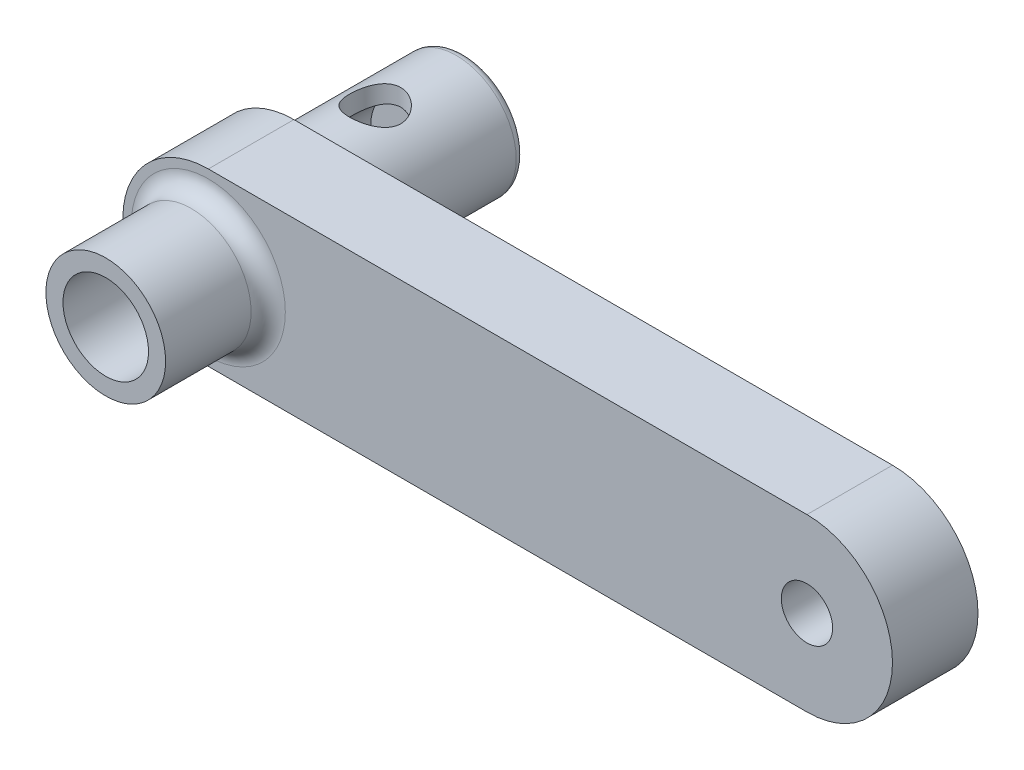
SolidWorks part; units mm, degrees
ref_plane "Plan de face" through (0, 0, 0) normal (0, 0, 1) x (1, 0, 0)
ref_plane "Plan de dessus" through (0, 0, 0) normal (0, 1, 0) x (1, 0, 0)
ref_plane "Plan de droite" through (0, 0, 0) normal (1, 0, 0) x (0, 0, -1)
sketch "Esquisse1" plane through (0, 0, 0) normal (0, 0, 1) x (1, 0, 0)
  line L0 (-17.5, 0) -> (17.5, 0) construction
  line L1 (-17.5, 5) -> (17.5, 5)
  line L2 (-17.5, -5) -> (17.5, -5)
  arc A0 (-17.5, 5) -> (-17.5, -5) centre (-17.5, 0) ccw
  arc A1 (17.5, -5) -> (17.5, 5) centre (17.5, 0) ccw
  circle A2 centre (-17.5, 0) radius 2.5
  circle A3 centre (17.5, 0) radius 1.5
  point P2 (0, 0)
  dimension "D2" = 5
  dimension "D3" = 5
  dimension "D4" = 3
  dimension "D1" = 35
extrude "Boss.-Extru.1" add sketch "Esquisse1" along normal blind 5
sketch "Esquisse2" plane through (0, 0, 5) normal (0, 0, 1) x (1, 0, 0)
  circle A0 centre (-17.5, 0) radius 2.5 construction
  circle A1 centre (-17.5, 0) radius 2.5
  circle A2 centre (-17.5, 0) radius 3.5
  dimension "D1" = 7
extrude "Boss.-Extru.2" add sketch "Esquisse2" against normal blind 10 from offset 5 offset against normal yes
sketch "Esquisse3" plane through (0, 0, -10) normal (0, 0, -1) x (-1, 0, 0)
  circle A0 centre (17.5, 0) radius 3.5
extrude "Boss.-Extru.3" add sketch "Esquisse3" against normal blind 3
fillet "Congé1" radius 0.5 1 edges at (-14, 0, -10)
sketch "Esquisse4" plane through (0, 0, 0) normal (0, 1, 0) x (1, 0, 0)
  line L0 (-17.5, 9.5) -> (-17.5, 0) construction
  line L1 (-14, 9.5) -> (-21, 9.5) construction
  circle A0 centre (-17.5, 4.75) radius 1.5
  dimension "D1" = 3
extrude "Enlèv. mat.-Extru.1" cut sketch "Esquisse4" against normal through all and the other way through all
sketch "Esquisse5" plane through (0, 0, 5) normal (0, 0, 1) x (1, 0, 0)
  circle A0 centre (-17.5, 0) radius 2.5 construction
  circle A1 centre (-17.5, 0) radius 2.5
  circle A2 centre (-17.5, 0) radius 3.5
  dimension "D1" = 7
extrude "Boss.-Extru.4" add sketch "Esquisse5" along normal blind 6
fillet "Congé2" radius 1 1 edges at (-14, 0, 5)
fillet "Congé3" radius 1 1 edges at (-14, 0, 0)
